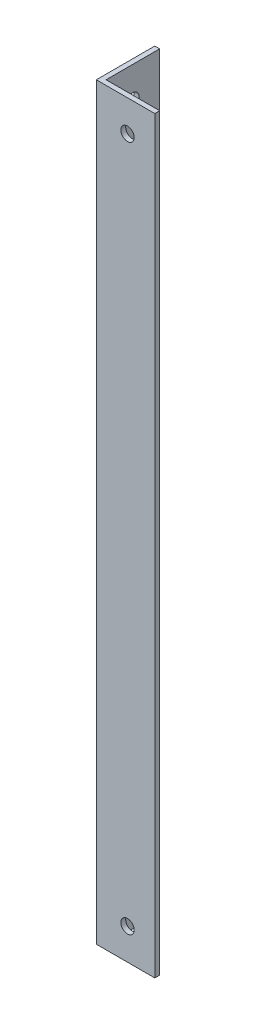
SolidWorks part; units mm, degrees
material "1060 Alloy"
ref_plane "Front Plane" through (0, 0, 0) normal (0, 0, 1) x (1, 0, 0)
ref_plane "Top Plane" through (0, 0, 0) normal (0, 1, 0) x (1, 0, 0)
ref_plane "Right Plane" through (0, 0, 0) normal (1, 0, 0) x (0, 0, -1)
sketch "Sketch1" plane through (0, 0, 0) normal (0, 1, 0) x (1, 0, 0)
  line L0 (0, 0) -> (0, 19.05)
  line L1 (0, 0) -> (19.05, 0)
  line L2 (19.05, 0) -> (19.05, 1.5875)
  line L3 (19.05, 1.5875) -> (1.5875, 1.5875)
  line L4 (1.5875, 1.5875) -> (1.5875, 19.05)
  line L5 (1.5875, 19.05) -> (0, 19.05)
  dimension "D1" = 19.05
  dimension "D2" = 1.5875
extrude "Boss-Extrude1" add sketch "Sketch1" along normal blind 243.84
sketch "Sketch2" plane through (0, 0, 0) normal (0, 0, 1) x (1, 0, 0)
  line L0 (0, 243.84) -> (19.05, 243.84) construction
  line L1 (0, 243.84) -> (0, 0) construction
  line L2 (0, 0) -> (19.05, 0) construction
  circle A0 centre (10.16, 233.68) radius 2.1828
  circle A1 centre (10.16, 10.16) radius 2.1828
  dimension "D1" = 4.3656
  dimension "D2" = 10.16
  dimension "D3" = 10.16
  dimension "D4" = 10.16
extrude "Cut-Extrude1" cut sketch "Sketch2" against normal blind 2.54
sketch "Sketch3" plane through (1.5875, 0, 0) normal (1, 0, 0) x (0, 0, -1)
  line L2 (1.5875, 233.68) -> (0, 233.68) construction
  line L3 (1.5875, 10.16) -> (0, 10.16) construction
  line L6 (0, 243.84) -> (0, 0) construction
  circle A0 centre (10.16, 233.68) radius 2.1828
  circle A1 centre (10.16, 10.16) radius 2.1828
  dimension "D1" = 4.3656
  dimension "D2" = 10.16
extrude "Cut-Extrude2" cut sketch "Sketch3" against normal through all
